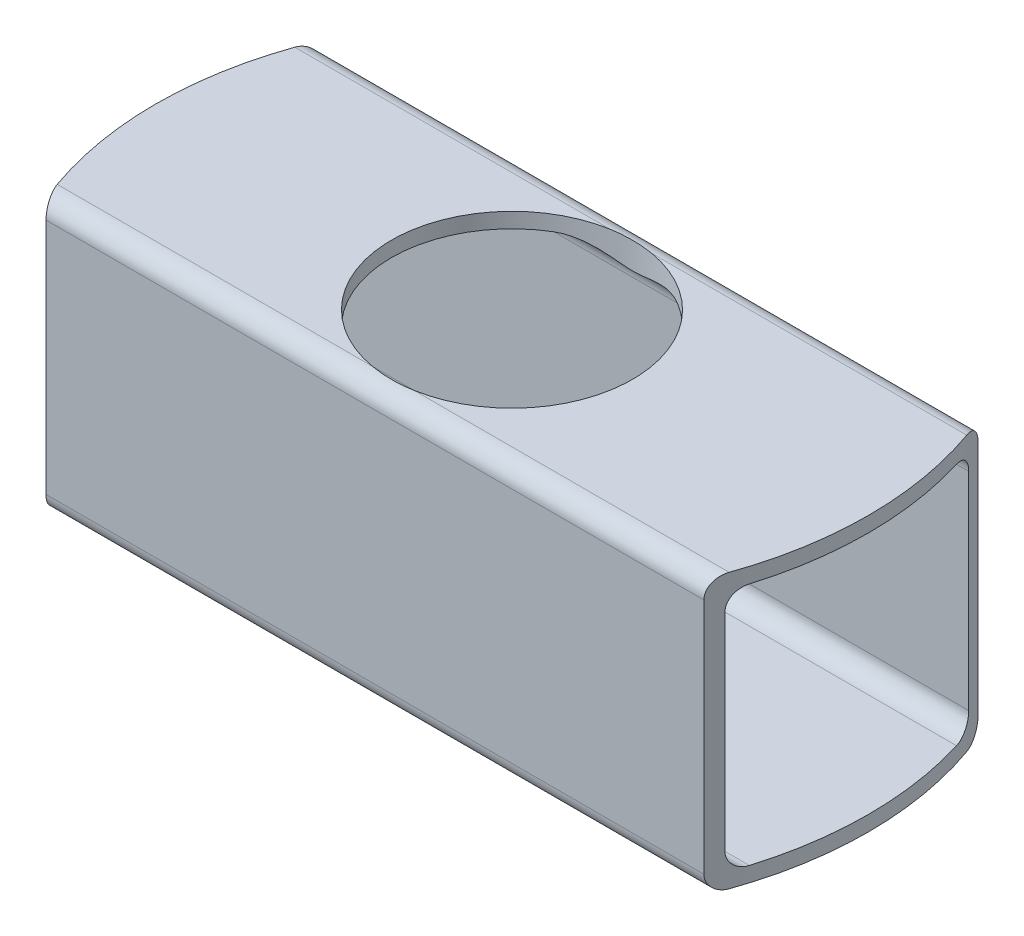
SolidWorks part; units mm, degrees
material "AISI 1020"
ref_plane "Front Plane" through (0, 0, 0) normal (0, 0, 1) x (1, 0, 0)
ref_plane "Top Plane" through (0, 0, 0) normal (0, 1, 0) x (1, 0, 0)
ref_plane "Right Plane" through (0, 0, 0) normal (1, 0, 0) x (0, 0, -1)
sketch "Sketch1" plane through (0, 0, 0) normal (1, 0, 0) x (0, 0, -1)
  line L0 (16.9418, 16.9418) -> (-16.9418, 16.9418)
  line L1 (19.05, -19.05) -> (-19.05, -19.05)
  line L2 (19.05, -19.05) -> (19.05, 19.05)
  line L3 (19.05, 19.05) -> (-19.05, 19.05)
  line L4 (-19.05, -19.05) -> (-19.05, 19.05)
  line L5 (19.05, -19.05) -> (-19.05, 19.05) construction
  line L6 (19.05, 19.05) -> (-19.05, -19.05) construction
  line L7 (-16.9418, -16.9418) -> (-16.9418, 16.9418)
  line L8 (16.9418, -16.9418) -> (-16.9418, -16.9418)
  line L9 (16.9418, -16.9418) -> (16.9418, 16.9418)
  point P0 (0, 0)
  point P10 (0, 0)
  dimension "D1" = 38.1
  dimension "D2" = 38.1
  dimension "D3" = 2.1082
extrude "Boss-Extrude1" add sketch "Sketch1" along normal mid plane 101.6
fillet "Fillet1" radius 2.54 8 edges at (0, -16.9418, -16.9418) (0, -16.9418, 16.9418) (0, 16.9418, -16.9418) (0, 16.9418, 16.9418) (0, -19.05, 19.05) (0, -19.05, -19.05) (0, 19.05, -19.05) (0, 19.05, 19.05)
sketch "Sketch3" plane through (0, 19.05, 0) normal (0, 1, 0) x (1, 0, 0)
  circle A0 centre (0, 0) radius 16.764
  dimension "D1" = 33.528
extrude "Cut-Extrude2" cut sketch "Sketch3" against normal through all
sketch "Sketch4" plane through (0, 19.05, 0) normal (0, 1, 0) x (1, 0, 0)
  line L1 (-50.8, 19.05) -> (50.8, 19.05)
  line L2 (-50.8, 19.05) -> (-50.8, -19.05)
  line L3 (-50.8, -19.05) -> (50.8, -19.05)
  line L4 (50.8, 19.05) -> (50.8, -19.05)
  circle A0 centre (0, 0) radius 49.53
  line M6 (50.8, 16.51) -> (2.9072, 16.51)
  line M8 (2.9072, -16.51) -> (50.8, -16.51)
  line M9 (50.8, -16.51) -> (50.8, 16.51)
  dimension "D1" = 99.06
extrude "Cut-Extrude3" cut sketch "Sketch4" against normal through all contours A0 L1 L2 L3 | A0 M8 M9 M6 | A0 L4 L1 M6 | A0 L3 L4 M8
